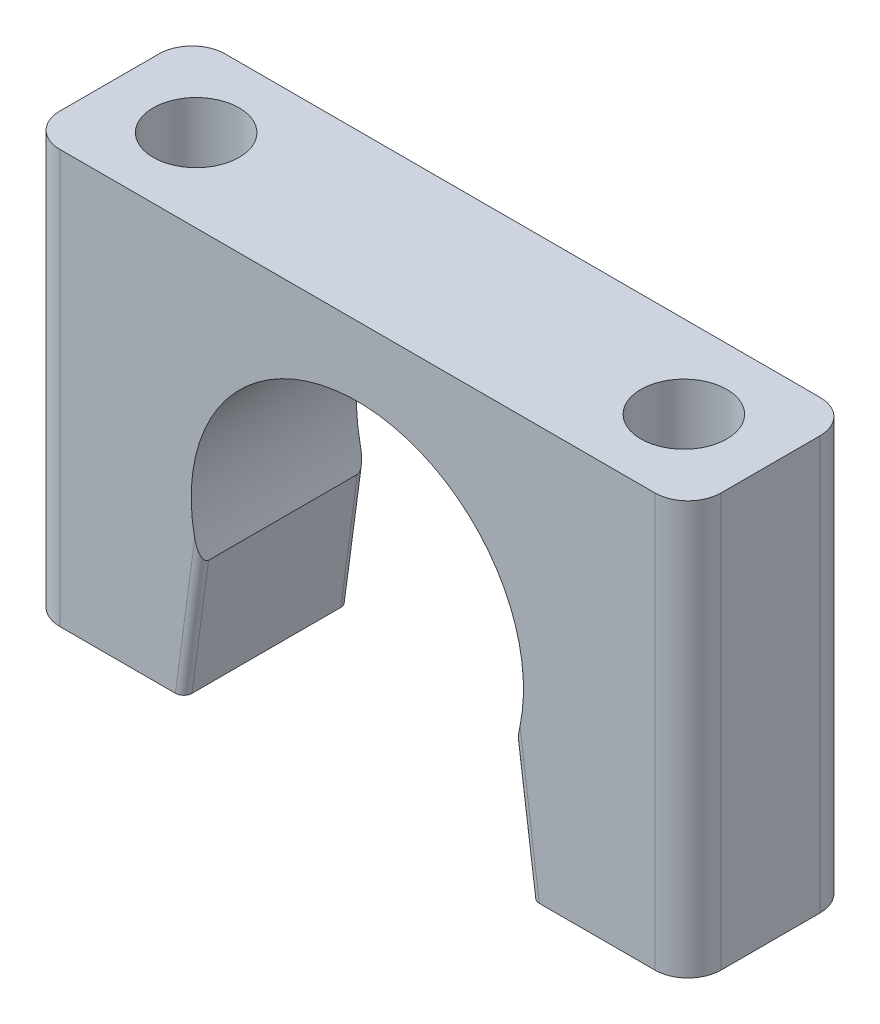
SolidWorks part; units mm, degrees
ref_plane "Front Plane" through (0, 0, 0) normal (0, 0, 1) x (1, 0, 0)
ref_plane "Top Plane" through (0, 0, 0) normal (0, 1, 0) x (1, 0, 0)
ref_plane "Right Plane" through (0, 0, 0) normal (1, 0, 0) x (0, 0, -1)
sketch "Sketch2" plane through (0, 0, 0) normal (0, 0, 1) x (1, 0, 0)
  line L0 (0, 10.05) -> (0, -10.75) construction
  line L1 (-9.5, -10.75) -> (9.5, -10.75) construction
  line L2 (9.5, -10.75) -> (9.5, -3.2791)
  line L3 (-20, -10.75) -> (-20, 14.25)
  line L4 (-20, 14.25) -> (20, 14.25)
  line L5 (20, -10.75) -> (20, 14.25)
  line L6 (-9.5, -10.75) -> (-9.5, -3.2791)
  line L7 (-20, -10.75) -> (-9.5, -10.75)
  line L8 (9.5, -10.75) -> (20, -10.75)
  line L9 (0, 10.05) -> (0, 14.25) construction
  arc A0 (9.5, -3.2791) -> (-9.5, -3.2791) centre (0, 0) ccw
  point P9 (0, -10.75)
  dimension "D1" = 20.1
  dimension "D2" = 25
  dimension "D3" = 40
  dimension "D4" = 19
  dimension "D5" = 4.2
extrude "Boss-Extrude2" add sketch "Sketch2" along normal blind 10
sketch "Sketch3" plane through (0, -10.75, 0) normal (0, -1, 0) x (1, 0, 0)
  line L0 (-20, 10) -> (-9.5, 0) construction
  line L1 (9.5, 0) -> (20, 10) construction
  circle A0 centre (-14.75, 5) radius 2.6
  circle A1 centre (14.75, 5) radius 2.6
  dimension "D1" = 5.2
extrude "Cut-Extrude1" cut sketch "Sketch3" against normal through all
fillet "Fillet1" radius 2 4 edges at (20, 1.75, 0) (20, 1.75, 10) (-20, 1.75, 0) (-20, 1.75, 10)
sketch "Sketch4" plane through (0, 0, 10) normal (0, 0, 1) x (1, 0, 0)
  line L0 (-9.5, -10.75) -> (-9.5, -3.2791)
  line L1 (9.5, -10.75) -> (9.5, -3.2791)
  line L2 (-9.5, -10.75) -> (-10.5, -10.75)
  line L3 (-18, -10.75) -> (-9.5, -10.75) construction
  line L4 (9.5, -10.75) -> (10.5, -10.75)
  line L5 (9.5, -10.75) -> (18, -10.75) construction
  line L6 (-9.5, -3.2791) -> (-10.5, -10.75)
  line L7 (9.5, -3.2791) -> (10.5, -10.75)
  dimension "D1" = 1
  dimension "D2" = 1
extrude "Cut-Extrude2" cut sketch "Sketch4" against normal through all
fillet "Fillet2" radius 0.5 4 edges at (10, -7.0146, 10) (10, -7.0146, 0) (-10, -7.0146, 10) (-10, -7.0146, 0)
